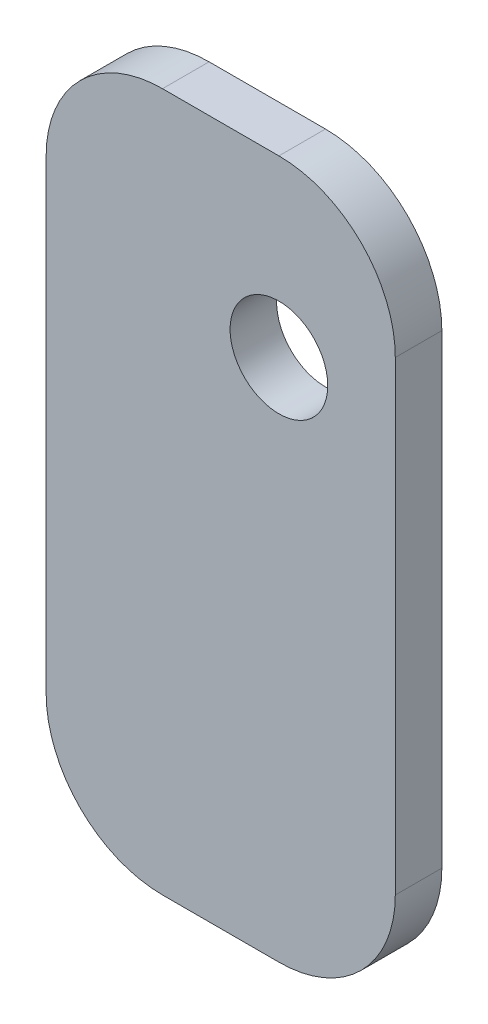
SolidWorks part; units mm, degrees
ref_plane "前基準面" through (0, 0, 0) normal (0, 0, 1) x (1, 0, 0)
ref_plane "上基準面" through (0, 0, 0) normal (0, 1, 0) x (1, 0, 0)
ref_plane "右基準面" through (0, 0, 0) normal (1, 0, 0) x (0, 0, -1)
sketch "草圖2" plane through (0, 0, 0) normal (0, 0, 1) x (1, 0, 0)
  line L1 (15, -30) -> (-15, -30)
  line L2 (15, -30) -> (15, 30)
  line L3 (15, 30) -> (-15, 30)
  line L4 (-15, -30) -> (-15, 30)
  line L5 (0, 30) -> (0, -30) construction
  line L6 (15, 0) -> (-15, 0) construction
  point P0 (0, 0)
  dimension "D1" = 60
  dimension "D2" = 30
extrude "填料-伸長1" add sketch "草圖2" along normal blind 4
sketch "草圖3" plane through (0, 0, 4) normal (0, 0, 1) x (1, 0, 0)
  line L0 (15, 30) -> (-15, 30) construction
  line L1 (15, -30) -> (15, 30) construction
  circle A0 centre (5, 15) radius 4.1951
  dimension "D1" = 15
  dimension "D2" = 10
extrude "除料-伸長1" cut sketch "草圖3" against normal through all
fillet "圓角1" radius 10 4 edges at (15, 30, 2) (-15, -30, 2) (15, -30, 2) (-15, 30, 2)
